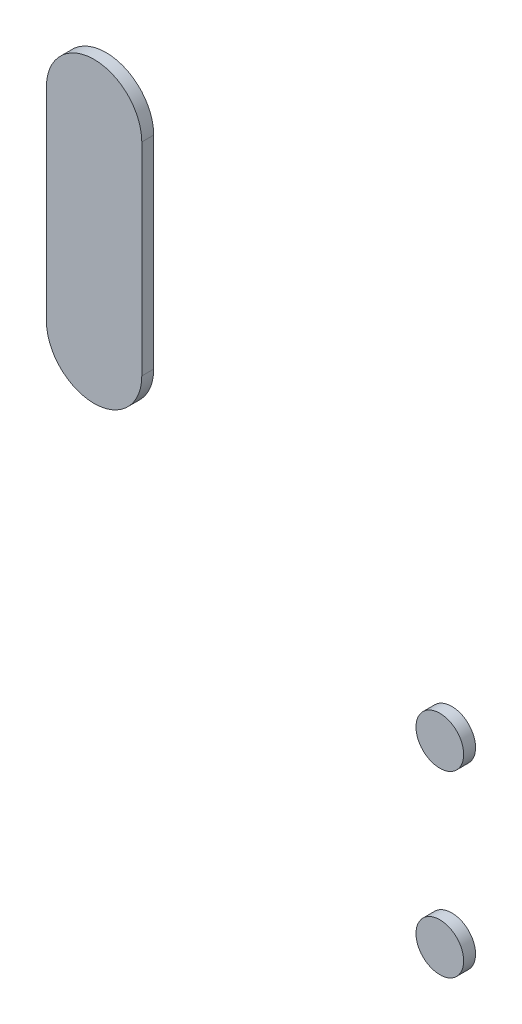
SolidWorks part; units mm, degrees
ref_plane "FP" through (0, 0, 0) normal (0, 0, 1) x (1, 0, 0)
ref_plane "TP" through (0, 0, 0) normal (0, 1, 0) x (1, 0, 0)
ref_plane "RP" through (0, 0, 0) normal (1, 0, 0) x (0, 0, -1)
sketch "Sketch1" plane through (0, 0, 0) normal (0, 0, 1) x (1, 0, 0)
  line L0 (4, 5) -> (4, 22) construction
  line L1 (-4, 22) -> (-4, 5) construction
  line L2 (4, 5) -> (4, 22)
  line L3 (-4, 22) -> (-4, 5)
  arc A0 (-4, 5) -> (4, 5) centre (0, 5) ccw construction
  arc A1 (4, 22) -> (-4, 22) centre (0, 22) ccw construction
  arc A2 (-4, 5) -> (4, 5) centre (0, 5) ccw
  arc A3 (4, 22) -> (-4, 22) centre (0, 22) ccw
  circle A4 centre (29, -24) radius 2 construction
  circle A5 centre (29, -9) radius 2 construction
  circle A6 centre (29, -24) radius 2
  circle A7 centre (29, -9) radius 2
extrude "Boss-Extrude1" add sketch "Sketch1" against normal blind 1
